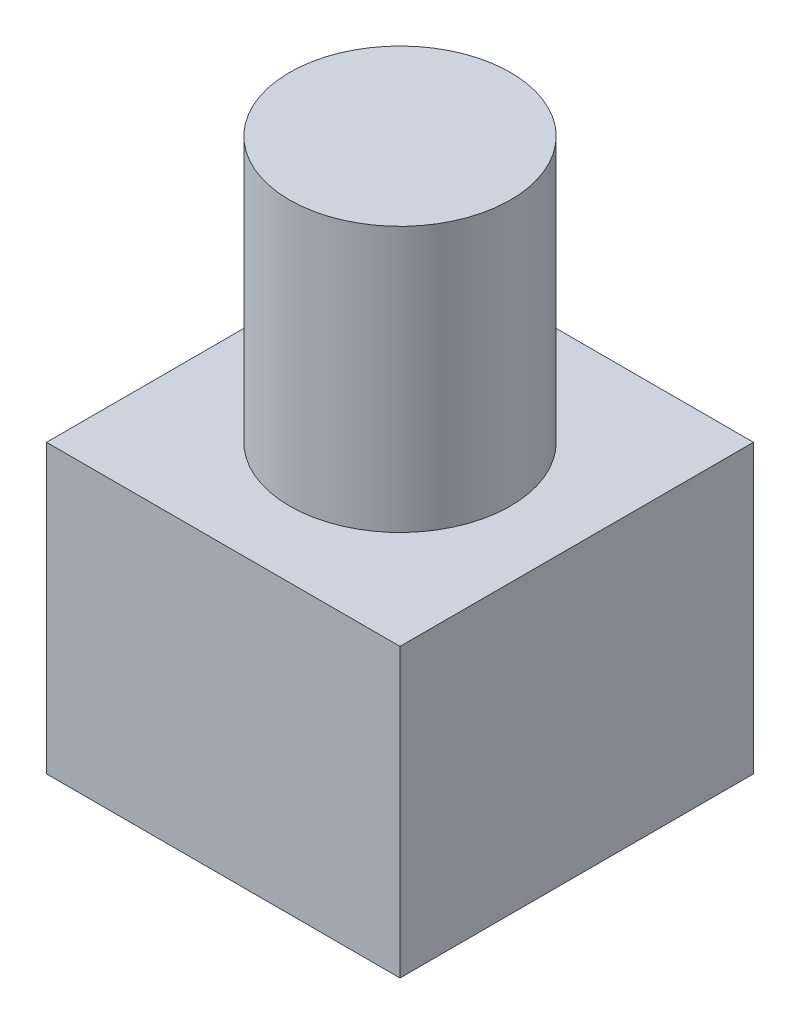
SolidWorks part; units mm, degrees
ref_plane "Płaszczyzna przednia" through (0, 0, 0) normal (0, 0, 1) x (1, 0, 0)
ref_plane "Płaszczyzna górna" through (0, 0, 0) normal (0, 1, 0) x (1, 0, 0)
ref_plane "Płaszczyzna prawa" through (0, 0, 0) normal (1, 0, 0) x (0, 0, -1)
sketch "Szkic1" plane through (0, 0, 0) normal (0, 1, 0) x (1, 0, 0)
  line L1 (-4, -4) -> (4, -4)
  line L2 (-4, -4) -> (-4, 4)
  line L3 (-4, 4) -> (4, 4)
  line L4 (4, -4) -> (4, 4)
  line L5 (-4, -4) -> (4, 4) construction
  line L6 (-4, 4) -> (4, -4) construction
  point P0 (0, 0)
  dimension "D1" = 8
extrude "Dodanie-wyciągnięcie1" add sketch "Szkic1" along normal blind 6.5
sketch "Szkic2" plane through (0, 6.5, 0) normal (0, 1, 0) x (1, 0, 0)
  circle A0 centre (0, 0) radius 2.5
  dimension "D1" = 5
extrude "Dodanie-wyciągnięcie2" add sketch "Szkic2" along normal blind 6
